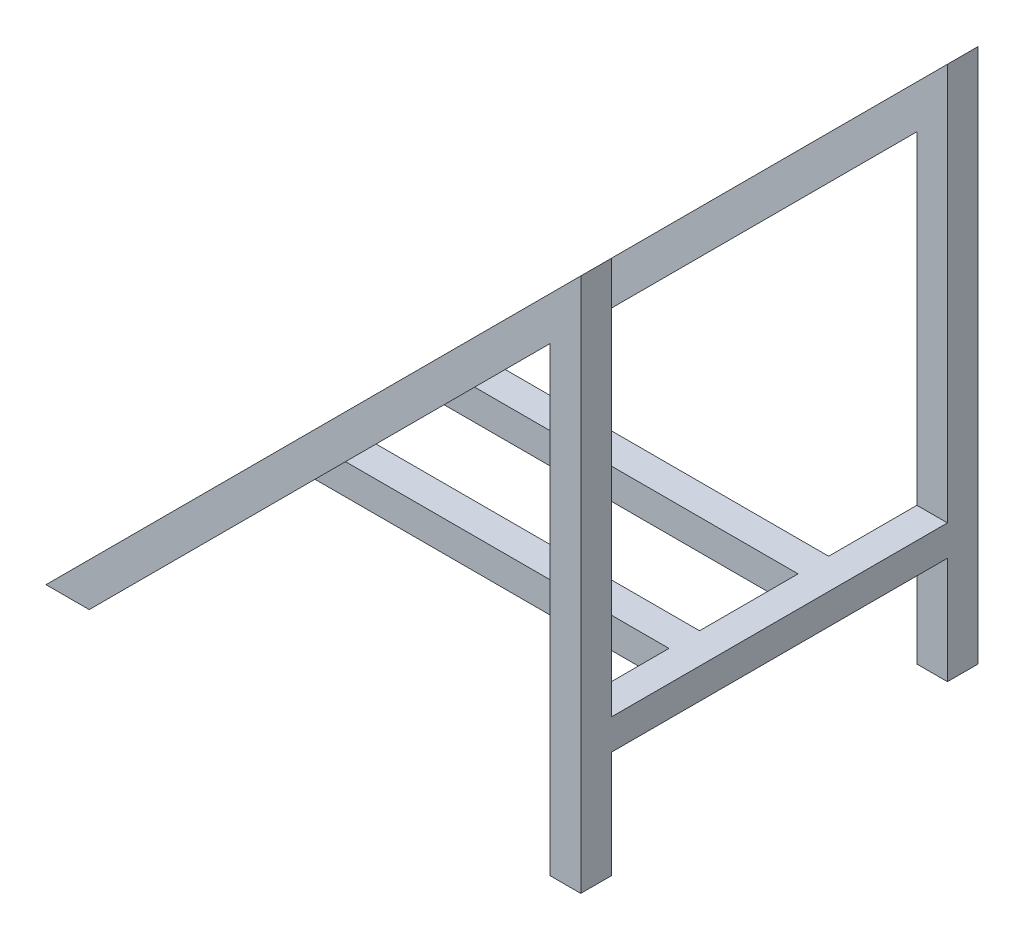
SolidWorks part; units mm, degrees
ref_plane "Front Plane" through (0, 0, 0) normal (0, 0, 1) x (1, 0, 0)
ref_plane "Top Plane" through (0, 0, 0) normal (0, 1, 0) x (1, 0, 0)
ref_plane "Right Plane" through (0, 0, 0) normal (1, 0, 0) x (0, 0, -1)
sketch "Sketch1" plane through (0, 0, 0) normal (0, 0, 1) x (1, 0, 0)
  line L0 (0, 0) -> (350, 350)
  line L1 (350, 350) -> (350, 0)
  line L2 (0, 0) -> (28.2843, 0)
  line L3 (28.2843, 0) -> (330, 301.7157)
  line L4 (330, 301.7157) -> (330, 0)
  line L5 (330, 0) -> (350, 0)
  dimension "D1" = 20
  dimension "D2" = 20
  dimension "D3" = 45
  dimension "D4" = 350
extrude "Boss-Extrude1" add sketch "Sketch1" along normal blind 20 contours L0 L1 L5 L4 L3 L2
sketch "Sketch2" plane through (0, 0, 20) normal (0, 0, 1) x (1, 0, 0)
  line L0 (330, 301.7157) -> (330, 0) construction
  line L1 (330, 70) -> (350, 70)
  line L2 (330, 70) -> (330, 90)
  line L3 (330, 90) -> (350, 90)
  line L4 (350, 70) -> (350, 90)
  line L5 (350, 350) -> (350, 0) construction
  line L6 (98.2843, 70) -> (112.4264, 84.1421)
  line L7 (98.2843, 70) -> (84.1421, 84.1421)
  line L8 (112.4264, 84.1421) -> (98.2843, 98.2843)
  line L9 (84.1421, 84.1421) -> (98.2843, 98.2843)
  line L10 (28.2843, 0) -> (330, 301.7157) construction
  line L12 (98.2843, 70) -> (98.2843, 98.2843) construction
  line L13 (350, 70) -> (330, 90) construction
  line L14 (330, 0) -> (350, 0) construction
  line L16 (0, 0) -> (28.2843, 0) construction
  line L19 (0, 0) -> (350, 350) construction
  point P14 (128.35, 114.0764)
  point P15 (340, 80)
  dimension "D1" = 20
  dimension "D2" = 20
  dimension "D3" = 80
  dimension "D4" = 70
extrude "Boss-Extrude2" add sketch "Sketch2" along normal blind 220
ref_plane "Plane1" through (0, 0, 130) normal (0, 0, -1) x (-1, 0, 0)
mirror "Mirror1" about plane through (0, 0, 130) normal (0, 0, -1) of "Boss-Extrude1"
ref_plane "Plane2" through (0, 0, 182.25) normal (0, 0, 1) x (1, 0, 0)
sketch "Sketch5" plane through (0, 0, 182.25) normal (0, 0, 1) x (1, 0, 0)
  line L0 (330, 301.7157) -> (330, 0) construction
  line L1 (330, 70) -> (98.2843, 70)
  line L2 (330, 70) -> (330, 90)
  line L3 (330, 90) -> (118.2843, 90)
  line L4 (98.2843, 70) -> (118.2843, 90)
  line L6 (28.2843, 0) -> (330, 301.7157) construction
  line L7 (28.2843, 0) -> (330, 301.7157) construction
  line L9 (330, 0) -> (350, 0) construction
  point P6 (330, 80)
  dimension "D1" = 80
  dimension "D2" = 20
extrude "Boss-Extrude3" add sketch "Sketch5" against normal blind 20
pattern_linear "LPattern1" count 2 spacing 84.5 along (0, 0, -1) of "Boss-Extrude3"
